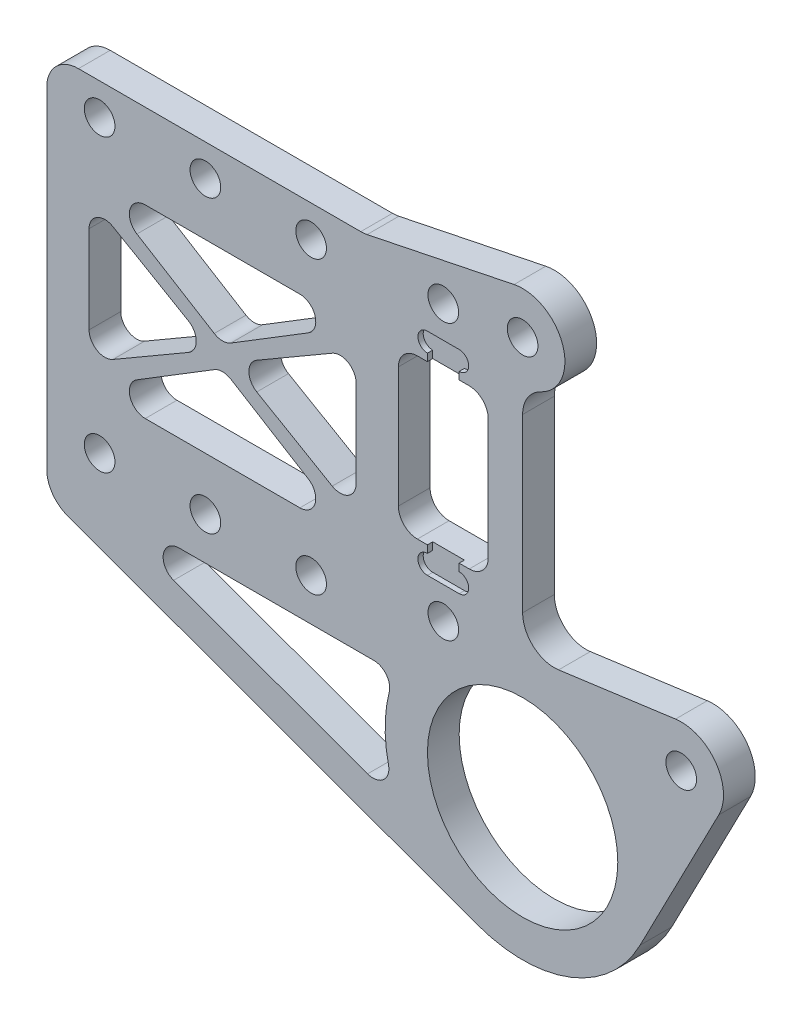
SolidWorks part; units mm, degrees
material "Thornel Mat VMA"
ref_plane "前视基准面" through (0, 0, 0) normal (0, 0, 1) x (1, 0, 0)
ref_plane "上视基准面" through (0, 0, 0) normal (0, 1, 0) x (1, 0, 0)
ref_plane "右视基准面" through (0, 0, 0) normal (1, 0, 0) x (0, 0, -1)
sketch "草图1" plane through (0, 0, 0) normal (0, 0, 1) x (1, 0, 0)
  line L0 (-20, -19) -> (20, -19)
  line L1 (-20, -20) -> (20, -20)
  line L2 (-20, -20) -> (-20, 20)
  line L3 (-20, 20) -> (20, 20)
  line L4 (20, -20) -> (20, 20)
  line L5 (-20, -20) -> (20, 20) construction
  line L6 (-20, 20) -> (20, -20) construction
  line L7 (-20, 15) -> (20, 15) construction
  line L8 (-20, 15) -> (-20, -5) construction
  line L9 (-20, -5) -> (20, -5) construction
  line L10 (20, 15) -> (20, -5) construction
  line L11 (-20, 25) -> (20, 25) construction
  line L12 (-20, 25) -> (-20, -35) construction
  line L13 (-20, -35) -> (20, -35) construction
  line L14 (20, 25) -> (20, -35) construction
  line L15 (-20, -34) -> (20, -34) construction
  line L16 (-20, -19.5) -> (20, -19.5)
  line L17 (-20, -7.89) -> (20, -7.89)
  line L18 (-20, -5.5) -> (20, -5.5)
  line L19 (20, -5) -> (51.2553, -5)
  circle A0 centre (35, -19.5) radius 12.5
  point P0 (0, 0)
  dimension "D5" = 25
  dimension "D6" = 15
  dimension "D1" = 40
  dimension "D2" = 40
  dimension "D3" = 20
  dimension "D4" = 5
  dimension "D7" = 60
  dimension "D8" = 5
  dimension "D9" = 1
  dimension "D10" = 1
  dimension "D11" = 0.5
  dimension "D12" = 14
  dimension "D13" = 2.39
sketch "草图2" plane through (0, 0, 0) normal (0, 0, 1) x (1, 0, 0)
  line L0 (-10, -7) -> (-10, -16.4236)
  line L4 (-20, -20) -> (20, -20) construction
  line L5 (-10, -16.4236) -> (30.7247, -31.2462)
  line L6 (-10, -7) -> (35, -7)
  line L7 (-10, -10.5) -> (20, -10.5) construction
  line L8 (20, -20) -> (20, 20) construction
  line L9 (-10, -10.5) -> (20, -10.5) construction
  line L10 (-10, -16) -> (20, -16) construction
  line L11 (-20, -5.5) -> (20, -5.5) construction
  circle A0 centre (35, -19.5) radius 9
  circle A1 centre (35, -19.5) radius 12.5 construction
  arc A2 (35, -7) -> (30.7247, -31.2462) centre (35, -19.5) cw
  circle A3 centre (15, -10.5) radius 1.45
  circle A4 centre (5, -10.5) radius 1.45
  circle A5 centre (-5, -10.5) radius 1.45
  dimension "D1" = 18
  dimension "D3" = 5
  dimension "D4" = 2.9
  dimension "D7" = 20
  dimension "D8" = 15
  dimension "D9" = 10
  dimension "D11" = 45
  dimension "D2" = 5
  dimension "D5" = 4
  dimension "D6" = 9.5
extrude "凸台-拉伸1" add sketch "草图2" along normal blind 3
sketch "草图4" plane through (0, 0, 3) normal (0, 0, 1) x (1, 0, 0)
  line L0 (20, -5) -> (51.2553, -5) construction
  line L1 (35, -7) -> (49.4618, -5.0364)
  line L2 (46.103, -25.2423) -> (53.5529, -10.8375)
  circle A0 centre (50, -9) radius 4 construction
  circle A1 centre (50, -9) radius 1.45
  circle A2 centre (35, -19.5) radius 12.5 construction
  arc A3 (49.4618, -5.0364) -> (53.5529, -10.8375) centre (50, -9) cw
  arc A4 (35, -7) -> (46.103, -25.2423) centre (35, -19.5) cw
  dimension "D1" = 8
  dimension "D2" = 2.9
  dimension "D3" = 15
extrude "凸台-拉伸2" add sketch "草图4" against normal blind 3
sketch "草图5" plane through (0, 0, 0) normal (0, 0, -1) x (-1, 0, 0)
  line L0 (-20, 15) -> (-35, 15) construction
  line L1 (-20, -20) -> (-20, 20) construction
  line L2 (-35, -7) -> (-35, 15)
  line L3 (-34.1945, 22.9181) -> (-20, 20)
  line L4 (-20, 20) -> (10, 20)
  line L5 (20, 20) -> (-20, 20) construction
  line L6 (10, -7) -> (10, -16.4236) construction
  line L7 (10, 20) -> (10, -7)
  line L8 (10, -7) -> (-35, -7)
  line L10 (-31.75, 12.5) -> (-23.25, 12.5)
  line L11 (-31.75, 12.5) -> (-31.75, -2.5)
  line L12 (-31.75, -2.5) -> (-23.25, -2.5)
  line L13 (-23.25, 12.5) -> (-23.25, -2.5)
  circle A0 centre (-35, 19) radius 4 construction
  circle A1 centre (-35, 19) radius 1.45
  arc A2 (-35, 15) -> (-34.1945, 22.9181) centre (-35, 19) cw
  dimension "D2" = 8
  dimension "D3" = 2.9
  dimension "D1" = 15
  dimension "D4" = 15
  dimension "D5" = 8.5
  dimension "D6" = 15
  dimension "D7" = 3.25
  dimension "D8" = 2.5
extrude "凸台-拉伸3" add sketch "草图5" against normal blind 3
sketch "草图6" plane through (0, 0, 3) normal (0, 0, 1) x (1, 0, 0)
  line L0 (27.5, 12.5) -> (27.5, -2.5) construction
  line L1 (23.25, 12.5) -> (31.75, 12.5) construction
  line L2 (31.75, -2.5) -> (23.25, -2.5) construction
  line L4 (26, -5) -> (29, -5)
  line L5 (26, -5) -> (26, 15)
  line L6 (26, 15) -> (29, 15)
  line L7 (29, -5) -> (29, 15)
  line L8 (26, -5) -> (29, 15) construction
  line L9 (26, 15) -> (29, -5) construction
  point P6 (27.5, 5)
  dimension "D1" = 3
  dimension "D2" = 20
extrude "切除-拉伸2" cut sketch "草图6" against normal blind 0.5
sketch "草图7" plane through (0, 0, 3) normal (0, 0, 1) x (1, 0, 0)
  line L0 (23.25, 5) -> (31.75, 5) construction
  line L1 (23.25, -2.5) -> (23.25, 12.5) construction
  line L2 (31.75, 12.5) -> (31.75, -2.5) construction
  line L3 (27.5, 5) -> (27.5, 18) construction
  line L4 (-20, 20) -> (20, 20) construction
  line L5 (-5, -10.5) -> (-5, 0) construction
  line L6 (5, -10.5) -> (5, 0) construction
  line L7 (15, -10.5) -> (15, 0) construction
  circle A0 centre (27.5, 18) radius 1.45
  circle A1 centre (27.5, -8) radius 1.45
  circle A2 centre (-5, 17) radius 1.45
  circle A3 centre (5, 17) radius 1.45
  circle A4 centre (15, 17) radius 1.45
  dimension "D2" = 2.9
  dimension "D3" = 3
  dimension "D4" = 2.9
  dimension "D1" = 13
extrude "切除-拉伸3" cut sketch "草图7" against normal blind 20
fillet "圆角1" radius 1.8 4 edges at (23.25, -2.5, 1.5) (31.75, -2.5, 1.5) (31.75, 12.5, 1.5) (23.25, 12.5, 1.5)
fillet "圆角2" radius 3 5 edges at (-10, -16.4236, 1.5) (-10, 20, 1.5) (35, 15, 1.5) (35, -7, 1.5) (20, 20, 1.5)
sketch "草图8" plane through (0, 0, 3) normal (0, 0, 1) x (1, 0, 0)
  line L0 (26, 15) -> (26, 12.5) construction
  line L1 (29, 12.5) -> (29, 15) construction
  line L2 (26, -2.5) -> (26, -5) construction
  line L3 (29, -5) -> (29, -2.5) construction
  circle A0 centre (26, 14.1) radius 0.9
  circle A1 centre (29, 14.1) radius 0.9
  circle A2 centre (26, -4.1) radius 0.9
  circle A3 centre (29, -4.1) radius 0.9
  dimension "D1" = 1.8
  dimension "D2" = 1.8
  dimension "D3" = 1.8
  dimension "D4" = 1.8
extrude "切除-拉伸4" cut sketch "草图8" against normal blind 0.5
sketch "草图9" plane through (0, 0, 0) normal (0, 0, -1) x (-1, 0, 0)
  line L0 (-23.25, -0.7) -> (-23.25, 10.7) construction
  line L1 (-20.25, 13) -> (7, 13) construction
  line L2 (-20.25, 13) -> (-20.25, -6.5) construction
  line L3 (-20.25, -6.5) -> (7, -6.5) construction
  line L4 (7, 13) -> (7, -6.5) construction
  line L5 (10, 17) -> (10, -14.3229) construction
  line L6 (-20.25, 3.25) -> (7, 3.25) construction
  line L7 (-6.625, 13) -> (-6.625, -6.5) construction
  line L8 (-6.625, 4.25) -> (-19.25, 12)
  line L9 (-19.25, 12) -> (6, 12)
  line L10 (6, 12) -> (-6.625, 4.25)
  line L11 (-7.625, 3.25) -> (-19.25, 10)
  line L12 (-19.25, 10) -> (-19.25, -3.5)
  line L13 (-19.25, -3.5) -> (-7.625, 3.25)
  line L14 (6, 10) -> (6, -3.5)
  line L15 (-5.625, 3.25) -> (6, 10)
  line L16 (6, -3.5) -> (-5.625, 3.25)
  line L17 (-19.25, -5.5) -> (6, -5.5)
  line L18 (-6.625, 2.25) -> (-19.25, -5.5)
  line L19 (6, -5.5) -> (-6.625, 2.25)
  line L20 (-23, -14.5) -> (6, -14.5)
  line L21 (6, -14.5) -> (-23.2987, -25.1638)
  line L22 (8.0261, -17.142) -> (-30.7247, -31.2462) construction
  circle A0 centre (-15, 17) radius 1.45 construction
  circle A1 centre (-5, -10.5) radius 1.45 construction
  circle A2 centre (-15, -10.5) radius 1.45 construction
  arc A3 (-23, -14.5) -> (-23.2987, -25.1638) centre (-35, -19.5) cw
  circle A4 centre (-35, -19.5) radius 9 construction
  dimension "D15" = 4
  dimension "D1" = 4
  dimension "D2" = 3
  dimension "D3" = 4
  dimension "D4" = 3
  dimension "D5" = 1
  dimension "D6" = 1
  dimension "D7" = 1
  dimension "D8" = 1
  dimension "D9" = 1
  dimension "D10" = 1
  dimension "D11" = 3
  dimension "D12" = 3
  dimension "D13" = 4
  dimension "D14" = 4
extrude "切除-拉伸5" cut sketch "草图9" against normal blind 10.5
fillet "圆角3" radius 1.5 15 edges at (-6, -14.5, 1.5) (23.2987, -25.1638, 1.5) (23, -14.5, 1.5) (-6, -5.5, 1.5) (19.25, -5.5, 1.5) (6.625, 2.25, 1.5) (-6, -3.5, 1.5) (-6, 10, 1.5) (5.625, 3.25, 1.5) (19.25, 12, 1.5) (-6, 12, 1.5) (6.625, 4.25, 1.5) (19.25, 10, 1.5) (7.625, 3.25, 1.5) (19.25, -3.5, 1.5)
